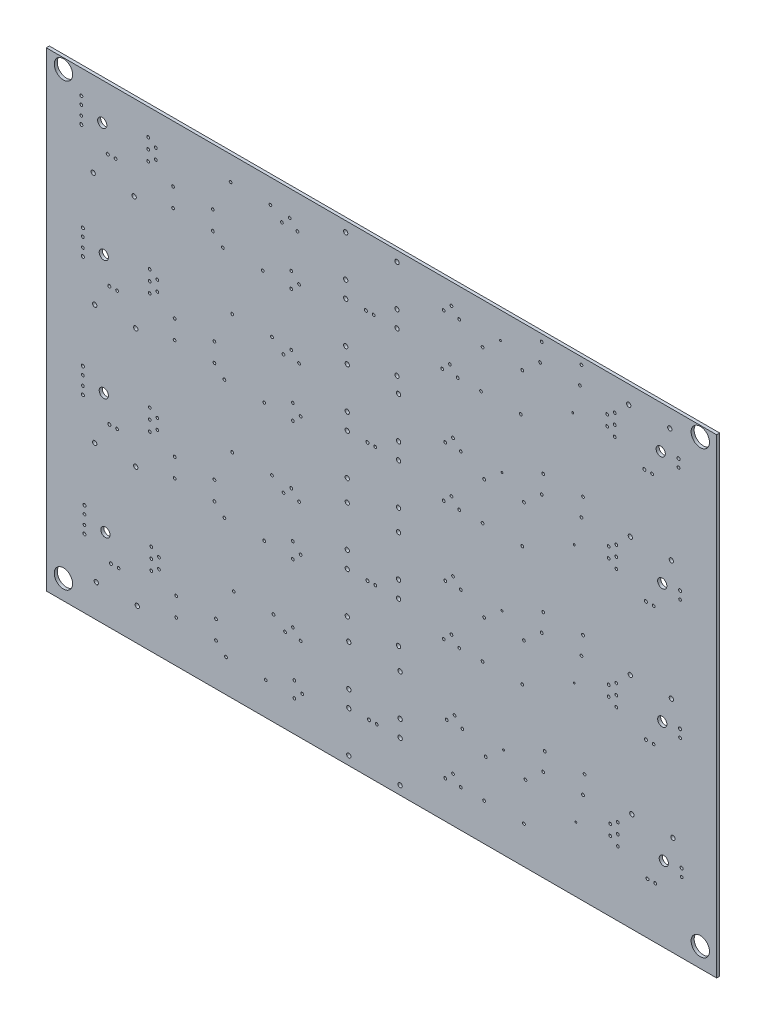
SolidWorks part; units mm, degrees
ref_plane "Plan de face" through (0, 0, 0) normal (0, 0, 1) x (1, 0, 0)
ref_plane "Plan de dessus" through (0, 0, 0) normal (0, 1, 0) x (1, 0, 0)
ref_plane "Plan de droite" through (0, 0, 0) normal (1, 0, 0) x (0, 0, -1)
sketch "Model" plane through (0, 0, 0) normal (0, 0, 1) x (1, 0, 0)
  line L0 (-2.286, -72.136) -> (216.662, -72.136)
  line L1 (216.662, -72.136) -> (216.662, 81.534)
  line L2 (216.662, 81.534) -> (-2.286, 81.534)
  line L3 (-2.286, 81.534) -> (-2.286, -72.136)
  circle A0 centre (211.328, 78.232) radius 3
  circle A1 centre (211.328, -65.786) radius 3
  circle A2 centre (3.302, -65.786) radius 3
  circle A3 centre (3.302, 78.232) radius 3
  circle A4 centre (169.672, 64.262) radius 0.3
  circle A5 centre (146.05, 72.898) radius 0.3
  circle A6 centre (95.504, 46.036) radius 0.6985
  circle A7 centre (95.504, 59.436) radius 0.6985
  circle A8 centre (112.268, 46.036) radius 0.6985
  circle A9 centre (112.268, 59.436) radius 0.6985
  circle A10 centre (80.264, 55.88) radius 0.4445
  circle A11 centre (77.724, 58.42) radius 0.4445
  circle A12 centre (77.724, 53.34) radius 0.4445
  circle A13 centre (129.54, 57.912) radius 0.4445
  circle A14 centre (127, 55.372) radius 0.4445
  circle A15 centre (132.08, 55.372) radius 0.4445
  circle A16 centre (26.416, 53.848) radius 0.6985
  circle A17 centre (13.016, 53.848) radius 0.6985
  circle A18 centre (102.108, 59.436) radius 0.4975
  circle A19 centre (104.648, 59.436) radius 0.4445
  circle A20 centre (30.988, 69.4478) radius 0.4445
  circle A21 centre (30.988, 72.8557) radius 0.4445
  circle A22 centre (33.4857, 71.1412) radius 0.4445
  circle A23 centre (30.988, 66.04) radius 0.4445
  circle A24 centre (33.4857, 67.7545) radius 0.4445
  circle A25 centre (15.9808, 69.4478) radius 1.5028
  circle A26 centre (183.388, 64.3043) radius 0.4445
  circle A27 centre (180.8903, 66.0188) radius 0.4445
  circle A28 centre (183.388, 71.12) radius 0.4445
  circle A29 centre (180.8903, 69.4055) radius 0.4445
  circle A30 centre (183.388, 67.7122) radius 0.4445
  circle A31 centre (198.3952, 67.7122) radius 1.5028
  circle A32 centre (187.96, 75.692) radius 0.6985
  circle A33 centre (201.36, 75.692) radius 0.6985
  circle A34 centre (95.504, 78.232) radius 0.6985
  circle A35 centre (95.504, 64.832) radius 0.6985
  circle A36 centre (112.268, 78.232) radius 0.6985
  circle A37 centre (112.268, 64.832) radius 0.6985
  circle A38 centre (77.216, 73.152) radius 0.4445
  circle A39 centre (74.676, 70.612) radius 0.4445
  circle A40 centre (79.756, 70.612) radius 0.4445
  circle A41 centre (130.048, 74.676) radius 0.4445
  circle A42 centre (132.588, 72.136) radius 0.4445
  circle A43 centre (127.508, 72.136) radius 0.4445
  circle A44 centre (172.512, 79.248) radius 0.45
  circle A45 centre (159.512, 79.248) radius 0.45
  circle A46 centre (68.372, 53.848) radius 0.45
  circle A47 centre (55.372, 53.848) radius 0.45
  circle A48 centre (152.7, 55.372) radius 0.45
  circle A49 centre (139.7, 55.372) radius 0.45
  circle A50 centre (52.116, 56.896) radius 0.45
  circle A51 centre (39.116, 56.896) radius 0.45
  circle A52 centre (52.116, 62.992) radius 0.45
  circle A53 centre (39.116, 62.992) radius 0.45
  circle A54 centre (153.208, 68.072) radius 0.45
  circle A55 centre (140.208, 68.072) radius 0.45
  circle A56 centre (70.912, 73.66) radius 0.45
  circle A57 centre (57.912, 73.66) radius 0.45
  circle A58 centre (172.004, 73.152) radius 0.45
  circle A59 centre (159.004, 73.152) radius 0.45
  circle A60 centre (96.012, 8.952) radius 0.6985
  circle A61 centre (96.012, 22.352) radius 0.6985
  circle A62 centre (112.776, 8.952) radius 0.6985
  circle A63 centre (112.776, 22.352) radius 0.6985
  circle A64 centre (80.772, 18.796) radius 0.4445
  circle A65 centre (78.232, 21.336) radius 0.4445
  circle A66 centre (78.232, 16.256) radius 0.4445
  circle A67 centre (68.88, 16.764) radius 0.45
  circle A68 centre (55.88, 16.764) radius 0.45
  circle A69 centre (130.048, 20.828) radius 0.4445
  circle A70 centre (127.508, 18.288) radius 0.4445
  circle A71 centre (132.588, 18.288) radius 0.4445
  circle A72 centre (153.208, 18.288) radius 0.45
  circle A73 centre (140.208, 18.288) radius 0.45
  circle A74 centre (13.524, 16.764) radius 0.6985
  circle A75 centre (26.924, 16.764) radius 0.6985
  circle A76 centre (52.624, 19.812) radius 0.45
  circle A77 centre (39.624, 19.812) radius 0.45
  circle A78 centre (102.616, 22.352) radius 0.4975
  circle A79 centre (105.156, 22.352) radius 0.4445
  circle A80 centre (18.288, 24.384) radius 0.4975
  circle A81 centre (20.828, 24.384) radius 0.4445
  circle A82 centre (52.624, 25.908) radius 0.45
  circle A83 centre (39.624, 25.908) radius 0.45
  circle A84 centre (31.496, 32.3638) radius 0.4445
  circle A85 centre (31.496, 35.7717) radius 0.4445
  circle A86 centre (33.9937, 34.0572) radius 0.4445
  circle A87 centre (31.496, 28.956) radius 0.4445
  circle A88 centre (33.9937, 30.6705) radius 0.4445
  circle A89 centre (16.4888, 32.3638) radius 1.5028
  circle A90 centre (96.012, 27.748) radius 0.6985
  circle A91 centre (96.012, 41.148) radius 0.6985
  circle A92 centre (112.776, 27.748) radius 0.6985
  circle A93 centre (112.776, 41.148) radius 0.6985
  circle A94 centre (170.18, 27.178) radius 0.3
  circle A95 centre (183.896, 27.2203) radius 0.4445
  circle A96 centre (181.3983, 28.9348) radius 0.4445
  circle A97 centre (183.896, 34.036) radius 0.4445
  circle A98 centre (181.3983, 32.3215) radius 0.4445
  circle A99 centre (183.896, 30.6282) radius 0.4445
  circle A100 centre (198.9032, 30.6282) radius 1.5028
  circle A101 centre (77.724, 36.068) radius 0.4445
  circle A102 centre (75.184, 33.528) radius 0.4445
  circle A103 centre (80.264, 33.528) radius 0.4445
  circle A104 centre (153.716, 30.988) radius 0.45
  circle A105 centre (140.716, 30.988) radius 0.45
  circle A106 centre (128.016, 35.052) radius 0.4445
  circle A107 centre (130.556, 37.592) radius 0.4445
  circle A108 centre (133.096, 35.052) radius 0.4445
  circle A109 centre (9.652, 34.036) radius 0.4445
  circle A110 centre (9.652, 36.576) radius 0.4975
  circle A111 centre (172.512, 36.068) radius 0.45
  circle A112 centre (159.512, 36.068) radius 0.45
  circle A113 centre (71.42, 36.576) radius 0.45
  circle A114 centre (58.42, 36.576) radius 0.45
  circle A115 centre (146.558, 35.814) radius 0.3
  circle A116 centre (188.468, 38.608) radius 0.6985
  circle A117 centre (201.868, 38.608) radius 0.6985
  circle A118 centre (173.02, 42.164) radius 0.45
  circle A119 centre (160.02, 42.164) radius 0.45
  circle A120 centre (96.012, -30.164) radius 0.6985
  circle A121 centre (96.012, -16.764) radius 0.6985
  circle A122 centre (112.776, -30.164) radius 0.6985
  circle A123 centre (112.776, -16.764) radius 0.6985
  circle A124 centre (80.772, -20.32) radius 0.4445
  circle A125 centre (78.232, -17.78) radius 0.4445
  circle A126 centre (78.232, -22.86) radius 0.4445
  circle A127 centre (68.88, -22.352) radius 0.45
  circle A128 centre (55.88, -22.352) radius 0.45
  circle A129 centre (130.048, -18.288) radius 0.4445
  circle A130 centre (127.508, -20.828) radius 0.4445
  circle A131 centre (132.588, -20.828) radius 0.4445
  circle A132 centre (153.208, -20.828) radius 0.45
  circle A133 centre (140.208, -20.828) radius 0.45
  circle A134 centre (13.524, -22.352) radius 0.6985
  circle A135 centre (26.924, -22.352) radius 0.6985
  circle A136 centre (52.624, -19.304) radius 0.45
  circle A137 centre (39.624, -19.304) radius 0.45
  circle A138 centre (102.616, -16.764) radius 0.4975
  circle A139 centre (105.156, -16.764) radius 0.4445
  circle A140 centre (18.288, -14.732) radius 0.4975
  circle A141 centre (20.828, -14.732) radius 0.4445
  circle A142 centre (52.624, -13.208) radius 0.45
  circle A143 centre (39.624, -13.208) radius 0.45
  circle A144 centre (31.496, -6.7522) radius 0.4445
  circle A145 centre (31.496, -3.3443) radius 0.4445
  circle A146 centre (33.9937, -5.0588) radius 0.4445
  circle A147 centre (31.496, -10.16) radius 0.4445
  circle A148 centre (33.9937, -8.4455) radius 0.4445
  circle A149 centre (16.4888, -6.7522) radius 1.5028
  circle A150 centre (96.012, -11.368) radius 0.6985
  circle A151 centre (96.012, 2.032) radius 0.6985
  circle A152 centre (112.776, -11.368) radius 0.6985
  circle A153 centre (112.776, 2.032) radius 0.6985
  circle A154 centre (170.18, -11.938) radius 0.3
  circle A155 centre (183.896, -11.8957) radius 0.4445
  circle A156 centre (181.3983, -10.1812) radius 0.4445
  circle A157 centre (183.896, -5.08) radius 0.4445
  circle A158 centre (181.3983, -6.7945) radius 0.4445
  circle A159 centre (183.896, -8.4878) radius 0.4445
  circle A160 centre (198.9032, -8.4878) radius 1.5028
  circle A161 centre (77.724, -3.048) radius 0.4445
  circle A162 centre (75.184, -5.588) radius 0.4445
  circle A163 centre (80.264, -5.588) radius 0.4445
  circle A164 centre (153.716, -8.128) radius 0.45
  circle A165 centre (140.716, -8.128) radius 0.45
  circle A166 centre (128.016, -4.064) radius 0.4445
  circle A167 centre (130.556, -1.524) radius 0.4445
  circle A168 centre (133.096, -4.064) radius 0.4445
  circle A169 centre (9.652, -5.08) radius 0.4445
  circle A170 centre (9.652, -2.54) radius 0.4975
  circle A171 centre (172.512, -3.048) radius 0.45
  circle A172 centre (159.512, -3.048) radius 0.45
  circle A173 centre (71.42, -2.54) radius 0.45
  circle A174 centre (58.42, -2.54) radius 0.45
  circle A175 centre (146.558, -3.302) radius 0.3
  circle A176 centre (188.468, -0.508) radius 0.6985
  circle A177 centre (201.868, -0.508) radius 0.6985
  circle A178 centre (173.02, 3.048) radius 0.45
  circle A179 centre (160.02, 3.048) radius 0.45
  circle A180 centre (96.52, -69.28) radius 0.6985
  circle A181 centre (96.52, -55.88) radius 0.6985
  circle A182 centre (113.284, -69.28) radius 0.6985
  circle A183 centre (113.284, -55.88) radius 0.6985
  circle A184 centre (81.28, -59.436) radius 0.4445
  circle A185 centre (78.74, -56.896) radius 0.4445
  circle A186 centre (78.74, -61.976) radius 0.4445
  circle A187 centre (69.388, -61.468) radius 0.45
  circle A188 centre (56.388, -61.468) radius 0.45
  circle A189 centre (130.556, -57.404) radius 0.4445
  circle A190 centre (128.016, -59.944) radius 0.4445
  circle A191 centre (133.096, -59.944) radius 0.4445
  circle A192 centre (153.716, -59.944) radius 0.45
  circle A193 centre (140.716, -59.944) radius 0.45
  circle A194 centre (14.032, -61.468) radius 0.6985
  circle A195 centre (27.432, -61.468) radius 0.6985
  circle A196 centre (53.132, -58.42) radius 0.45
  circle A197 centre (40.132, -58.42) radius 0.45
  circle A198 centre (53.132, -52.324) radius 0.45
  circle A199 centre (40.132, -52.324) radius 0.45
  circle A200 centre (32.004, -45.8682) radius 0.4445
  circle A201 centre (32.004, -42.4603) radius 0.4445
  circle A202 centre (34.5017, -44.1748) radius 0.4445
  circle A203 centre (32.004, -49.276) radius 0.4445
  circle A204 centre (34.5017, -47.5615) radius 0.4445
  circle A205 centre (16.9968, -45.8682) radius 1.5028
  circle A206 centre (96.52, -50.484) radius 0.6985
  circle A207 centre (96.52, -37.084) radius 0.6985
  circle A208 centre (113.284, -50.484) radius 0.6985
  circle A209 centre (113.284, -37.084) radius 0.6985
  circle A210 centre (170.688, -51.054) radius 0.3
  circle A211 centre (184.404, -51.0117) radius 0.4445
  circle A212 centre (181.9063, -49.2972) radius 0.4445
  circle A213 centre (184.404, -44.196) radius 0.4445
  circle A214 centre (181.9063, -45.9105) radius 0.4445
  circle A215 centre (184.404, -47.6038) radius 0.4445
  circle A216 centre (199.4112, -47.6038) radius 1.5028
  circle A217 centre (78.232, -42.164) radius 0.4445
  circle A218 centre (75.692, -44.704) radius 0.4445
  circle A219 centre (80.772, -44.704) radius 0.4445
  circle A220 centre (154.224, -47.244) radius 0.45
  circle A221 centre (141.224, -47.244) radius 0.45
  circle A222 centre (128.524, -43.18) radius 0.4445
  circle A223 centre (131.064, -40.64) radius 0.4445
  circle A224 centre (133.604, -43.18) radius 0.4445
  circle A225 centre (173.02, -42.164) radius 0.45
  circle A226 centre (160.02, -42.164) radius 0.45
  circle A227 centre (71.928, -41.656) radius 0.45
  circle A228 centre (58.928, -41.656) radius 0.45
  circle A229 centre (147.066, -42.418) radius 0.3
  circle A230 centre (188.976, -39.624) radius 0.6985
  circle A231 centre (202.376, -39.624) radius 0.6985
  circle A232 centre (173.528, -36.068) radius 0.45
  circle A233 centre (160.528, -36.068) radius 0.45
  circle A234 centre (103.124, -55.88) radius 0.4975
  circle A235 centre (105.664, -55.88) radius 0.4445
  circle A236 centre (10.16, -44.196) radius 0.4445
  circle A237 centre (10.16, -41.656) radius 0.4975
  circle A238 centre (18.796, -53.848) radius 0.4975
  circle A239 centre (21.336, -53.848) radius 0.4445
  circle A240 centre (196.596, -55.372) radius 0.4445
  circle A241 centre (194.056, -55.372) radius 0.4975
  circle A242 centre (205.232, -49.276) radius 0.4445
  circle A243 centre (205.232, -46.736) radius 0.4975
  circle A244 centre (196.088, -16.256) radius 0.4445
  circle A245 centre (193.548, -16.256) radius 0.4975
  circle A246 centre (204.724, -10.16) radius 0.4445
  circle A247 centre (204.724, -7.62) radius 0.4975
  circle A248 centre (204.724, 28.956) radius 0.4445
  circle A249 centre (204.724, 31.496) radius 0.4975
  circle A250 centre (196.088, 22.86) radius 0.4445
  circle A251 centre (193.548, 22.86) radius 0.4975
  circle A252 centre (9.144, 71.12) radius 0.4445
  circle A253 centre (9.144, 73.66) radius 0.4975
  circle A254 centre (17.78, 61.468) radius 0.4975
  circle A255 centre (20.32, 61.468) radius 0.4445
  circle A256 centre (195.58, 59.944) radius 0.4445
  circle A257 centre (193.04, 59.944) radius 0.4975
  circle A258 centre (204.216, 66.04) radius 0.4445
  circle A259 centre (204.216, 68.58) radius 0.4975
  circle A260 centre (10.16, -47.244) radius 0.4445
  circle A261 centre (10.16, -49.784) radius 0.4975
  circle A262 centre (9.652, -8.128) radius 0.4445
  circle A263 centre (9.652, -10.668) radius 0.4975
  circle A264 centre (9.652, 30.988) radius 0.4445
  circle A265 centre (9.652, 28.448) radius 0.4975
  circle A266 centre (9.144, 68.072) radius 0.4445
  circle A267 centre (9.144, 65.532) radius 0.4975
  circle A268 centre (211.328, 78.232) radius 3
  circle A269 centre (211.328, -65.786) radius 3
  circle A270 centre (3.302, -65.786) radius 3
  circle A271 centre (3.302, 78.232) radius 3
extrude "Boss-Extrude1" add sketch "Model" along normal blind 1
